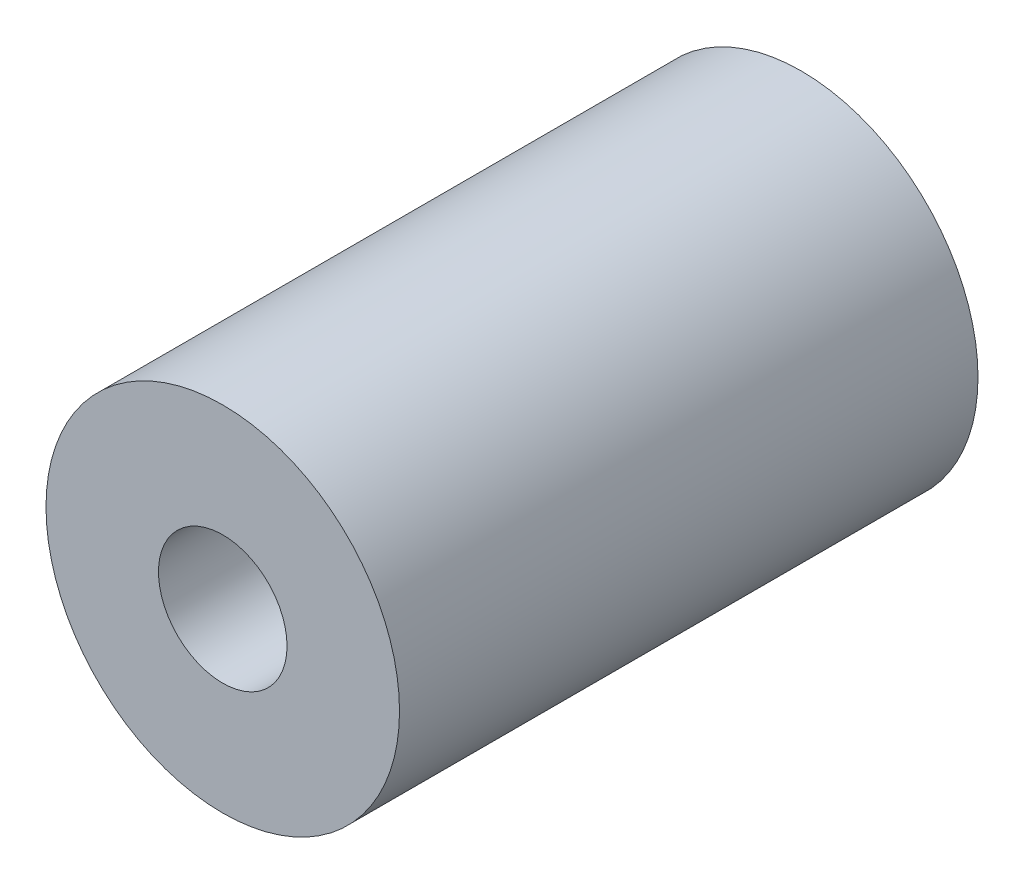
SolidWorks part; units mm, degrees
ref_plane "Front Plane" through (0, 0, 0) normal (0, 0, 1) x (1, 0, 0)
ref_plane "Top Plane" through (0, 0, 0) normal (0, 1, 0) x (1, 0, 0)
ref_plane "Right Plane" through (0, 0, 0) normal (1, 0, 0) x (0, 0, -1)
sketch "Sketch1" plane through (0, 0, 0) normal (0, 0, 1) x (1, 0, 0)
  circle A0 centre (0, 0) radius 11
  circle A1 centre (0, 0) radius 4
  dimension "D1" = 22
  dimension "D2" = 8
extrude "Boss-Extrude1" add sketch "Sketch1" along normal blind 36
